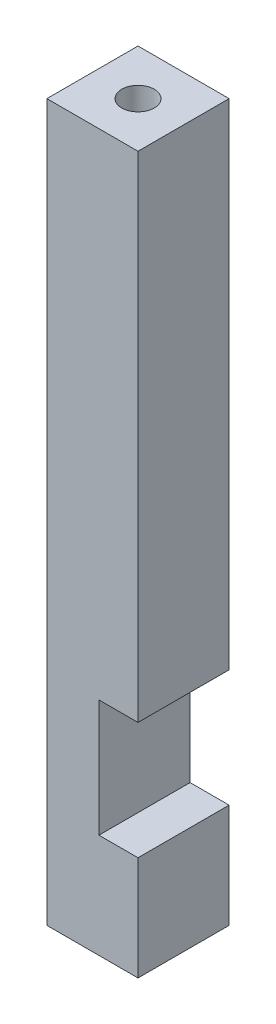
SolidWorks part; units mm, degrees
ref_plane "Front Plane" through (0, 0, 0) normal (0, 0, 1) x (1, 0, 0)
ref_plane "Top Plane" through (0, 0, 0) normal (0, 1, 0) x (1, 0, 0)
ref_plane "Right Plane" through (0, 0, 0) normal (1, 0, 0) x (0, 0, -1)
sketch "Sketch1" plane through (0, 0, 0) normal (0, 1, 0) x (1, 0, 0)
  line L0 (0, 3.5) -> (-3.5, 3.5)
  line L1 (-3.5, 3.5) -> (-3.5, -3.5)
  line L2 (-3.5, -3.5) -> (3.5, -3.5)
  line L3 (3.5, -3.5) -> (3.5, 3.5)
  line L4 (3.5, 3.5) -> (0, 3.5)
extrude "Boss-Extrude1" add sketch "Sketch1" along normal blind 55
sketch "Sketch2" plane through (0, 55, 0) normal (0, 1, 0) x (1, 0, 0)
  circle A0 centre (0, 0) radius 1.25
extrude "Cut-Extrude1" cut sketch "Sketch2" against normal blind 12 contours A0
sketch "Sketch3" plane through (0, 0, 0) normal (0, -1, 0) x (1, 0, 0)
  circle A0 centre (0, 0) radius 1.25
sketch "Sketch4" plane through (3.5, 0, 0) normal (1, 0, 0) x (0, 0, -1)
  line L0 (-3.5, 0) -> (-3.5, 8)
  line L1 (-3.5, 55) -> (-3.5, 0) construction
  line L2 (-3.5, 8) -> (3.5, 8)
  line L3 (3.5, 55) -> (3.5, 0) construction
  line L4 (3.5, 8) -> (3.5, 17)
  line L5 (3.5, 17) -> (-3.5, 17)
  line L6 (-3.5, 17) -> (-3.5, 8)
  line M7 (3.5, 0) -> (3.5, 55)
  line M9 (-3.5, 55) -> (-3.5, 0)
extrude "Cut-Extrude3" cut sketch "Sketch4" against normal blind 3 contours L5 L2 M7 M9
extrude "Cut-Extrude4" cut sketch "Sketch3" against normal blind 5 contours A0
